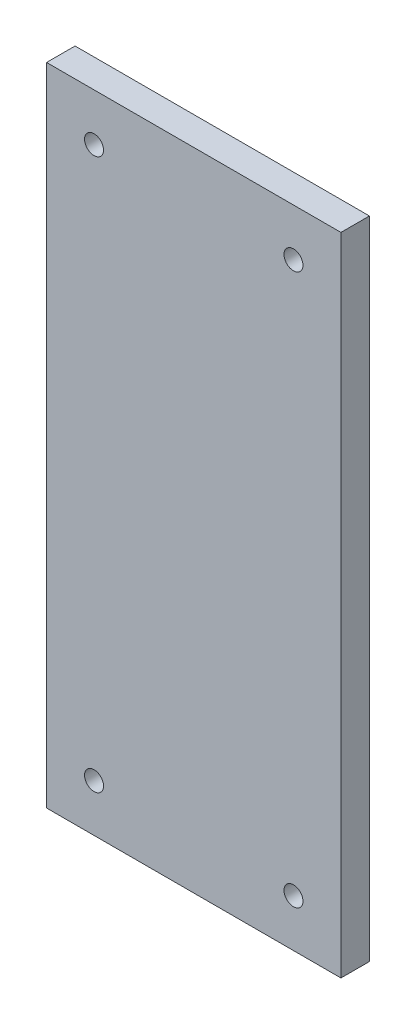
SolidWorks part; units mm, degrees
ref_plane "Plan de face" through (0, 0, 0) normal (0, 0, 1) x (1, 0, 0)
ref_plane "Plan de dessus" through (0, 0, 0) normal (0, 1, 0) x (1, 0, 0)
ref_plane "Plan de droite" through (0, 0, 0) normal (1, 0, 0) x (0, 0, -1)
sketch "Esquisse1" plane through (0, 0, 0) normal (0, 0, 1) x (1, 0, 0)
  line L0 (0, 0) -> (0, 68)
  line L1 (0, 68) -> (31, 68)
  line L2 (31, 68) -> (31, 0)
  line L3 (31, 0) -> (0, 0)
  dimension "D1" = 68
  dimension "D2" = 31
extrude "Boss.-Extru.1" add sketch "Esquisse1" along normal blind 3
hole_wizard "Trou taraudé #0-801" positions "Esquisse2" profile "Esquisse3" tap size "#0-80" standard "PCS" end condition through all
sketch "Esquisse2" plane through (0, 0, 3) normal (0, 0, 1) x (1, 0, 0)
  line L0 (0, 68) -> (0, 0) construction
  line L1 (31, 68) -> (0, 68) construction
  line L2 (31, 0) -> (31, 68) construction
  line L3 (0, 0) -> (31, 0) construction
  point P0 (5, 63)
  point P2 (26, 63)
  point P4 (26, 5)
  point P6 (5, 5)
  point P16 (24.9249, 63)
  point P17 (0, 0)
  dimension "D1" = 5
  dimension "D2" = 5
  dimension "D3" = 5
  dimension "D4" = 5
  dimension "D5" = 5
  dimension "D6" = 5
  dimension "D7" = 5
  dimension "D8" = 5
sketch "Esquisse3" plane through (5, 63, 3) normal (1, 0, 0) x (0, -1, 0)
  line L0 (0, 0) -> (0, 3)
  line L1 (0, 3) -> (1, 3)
  line L2 (1, 3) -> (1, 0)
  line L5 (1, 0) -> (0, 0)
  line L11 (0, -6.35) -> (0, 107.95) construction
  dimension "Diamètre du trou pour taraudage jusqu'au prochain" = 2
  dimension "Profondeur du trou pour taraudage jusqu'au prochain" = 3
cosmetic thread "Filetage de perçage1" parameters "D2"=2.3327
cosmetic thread "Filetage de perçage2" parameters "D2"=2.3327
cosmetic thread "Filetage de perçage3" parameters "D2"=2.3327
cosmetic thread "Filetage de perçage4" parameters "D2"=2.3327
